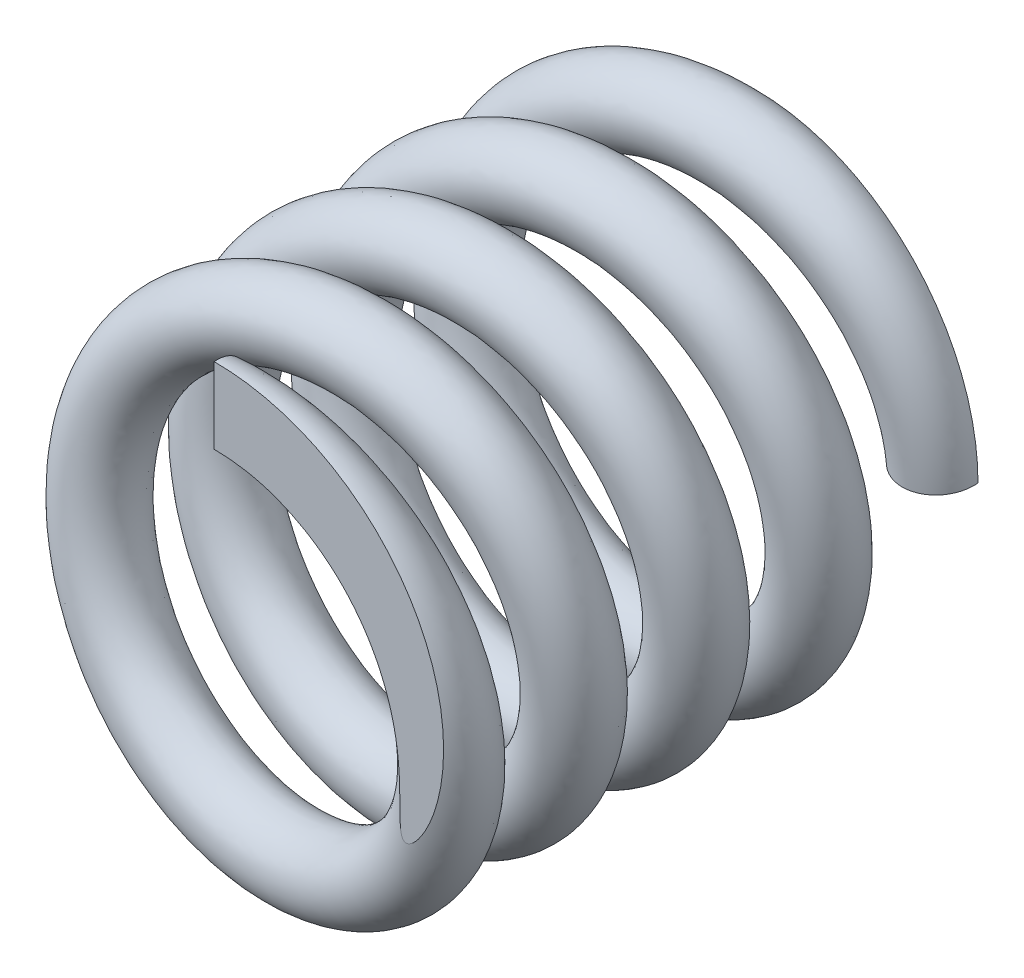
SolidWorks part; units mm, degrees
material "1.8519 (31CrMoV9)"
ref_plane "Ön Düzlem" through (0, 0, 0) normal (0, 0, 1) x (1, 0, 0)
ref_plane "Üst Düzlem" through (0, 0, 0) normal (0, 1, 0) x (1, 0, 0)
ref_plane "Sağ Düzlem" through (0, 0, 0) normal (1, 0, 0) x (0, 0, -1)
sketch "Çizim1" plane through (0, 0, 0) normal (0, 0, 1) x (1, 0, 0)
  circle A0 centre (0, 0) radius 6.7
  dimension "D1" = 13.4
curve "Helis/Spiral1" pitch 4 height 17 turns 4.25
ref_plane "Düzlem1" through (0, 6.7, 0) normal (0.9955, 0, -0.0946) x (-0.0946, 0, -0.9955)
sketch "Çizim3" plane through (0, 6.7, 0) normal (0.9955, 0, -0.0946) x (-0.0946, 0, -0.9955)
  circle A0 centre (0, 0.0172) radius 1.24
  dimension "D1" = 2.48
sweep "Süpür1" add profiles "Çizim3" path "Helis/Spiral1"
sketch "Çizim4" plane through (0, 0, 0) normal (0, 1, 0) x (1, 0, 0)
  line L0 (9.7126, 17) -> (-8.6759, 17)
  line L1 (-8.6759, 17) -> (-8.6759, 20.4903)
  line L2 (-8.6759, 20.4903) -> (9.7126, 20.4903)
  line L3 (9.7126, 20.4903) -> (9.7126, 17)
  line L4 (9.7126, 0) -> (9.7126, -3.1725)
  line L5 (9.7126, -3.1725) -> (-8.6759, -3.1725)
  line L6 (-8.6759, -3.1725) -> (-8.6759, 0)
  line L7 (-8.6759, 0) -> (9.7126, 0)
extrude "Kes-Ekstrüzyon1" cut sketch "Çizim4" against normal through all both and the other way through all
